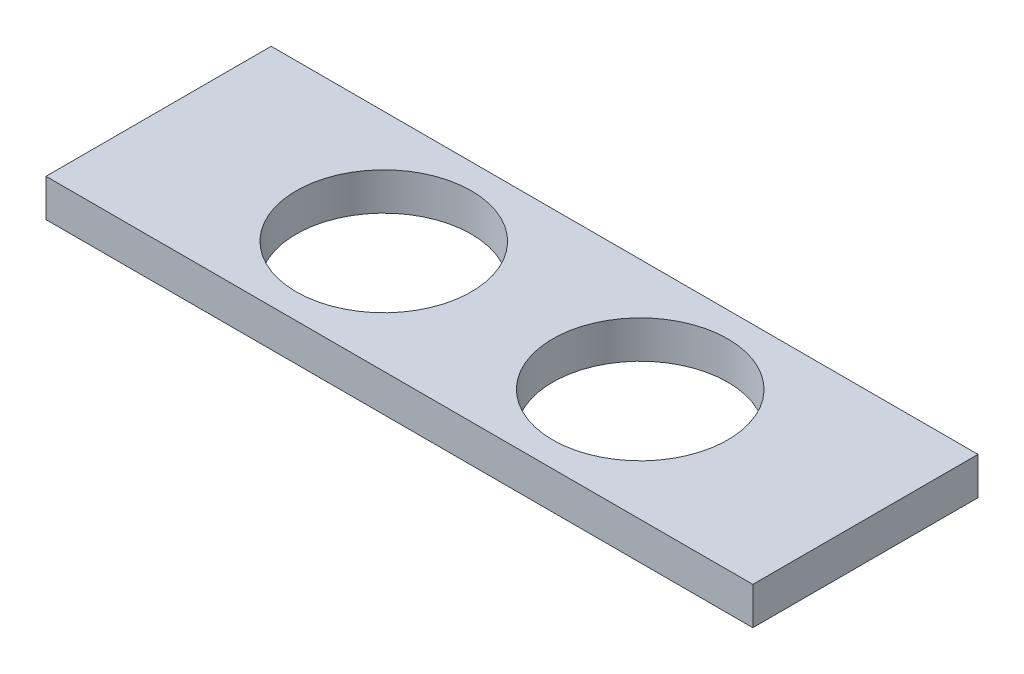
SolidWorks part; units mm, degrees
ref_plane "Front Plane" through (0, 0, 0) normal (0, 0, 1) x (1, 0, 0)
ref_plane "Top Plane" through (0, 0, 0) normal (0, 1, 0) x (1, 0, 0)
ref_plane "Right Plane" through (0, 0, 0) normal (1, 0, 0) x (0, 0, -1)
sketch "Sketch1" plane through (0, 0, 0) normal (0, 1, 0) x (1, 0, 0)
  line L0 (-3, 0) -> (-3, 50000) construction
  line L1 (3, 0) -> (3, 50000) construction
  line L2 (5, 0) -> (5, 50000) construction
  line L3 (-30.5, 9) -> (5.5, 9)
  line L4 (-30.5, 9) -> (-30.5, -9)
  line L5 (-30.5, -9) -> (5.5, -9)
  line L6 (5.5, 9) -> (5.5, -9) construction
  line L7 (-5, 0) -> (-5, 50000) construction
  line L9 (26, 9) -> (-10, 9)
  line L10 (26, 9) -> (26, -9)
  line L11 (26, -9) -> (-10, -9)
  line L12 (-10, 9) -> (-10, -9) construction
  line L13 (-30.5, 9) -> (26, 9)
  line L14 (-30.5, 9) -> (-30.5, -9)
  line L15 (-30.5, -9) -> (26, -9)
  line L16 (26, 9) -> (26, -9)
  circle A0 centre (0, 0) radius 3 construction
  circle A1 centre (-12.5, 0) radius 7
  circle A2 centre (8, 0) radius 7
  circle A3 centre (-10, 0) radius 15 construction
  circle A4 centre (10, 0) radius 15 construction
  point P11 (-30.5, 0)
  point P18 (-12.5, 9)
  point P25 (9.3539, 9)
  point P26 (8, 9)
  point P28 (26, 0)
  dimension "D1" = 6
  dimension "D2" = 36
  dimension "D5" = 14
  dimension "D6" = 14
  dimension "D9" = 2
  dimension "D7" = 2
  dimension "D8" = 7
  dimension "D10" = 12.5
  dimension "D3" = 7
  dimension "D4" = 18
  dimension "D11" = 8
  dimension "D12" = 36
extrude "Boss-Extrude2" add sketch "Sketch1" along normal blind 3 contours A2 | L14 L13 L16 L15 | A1
